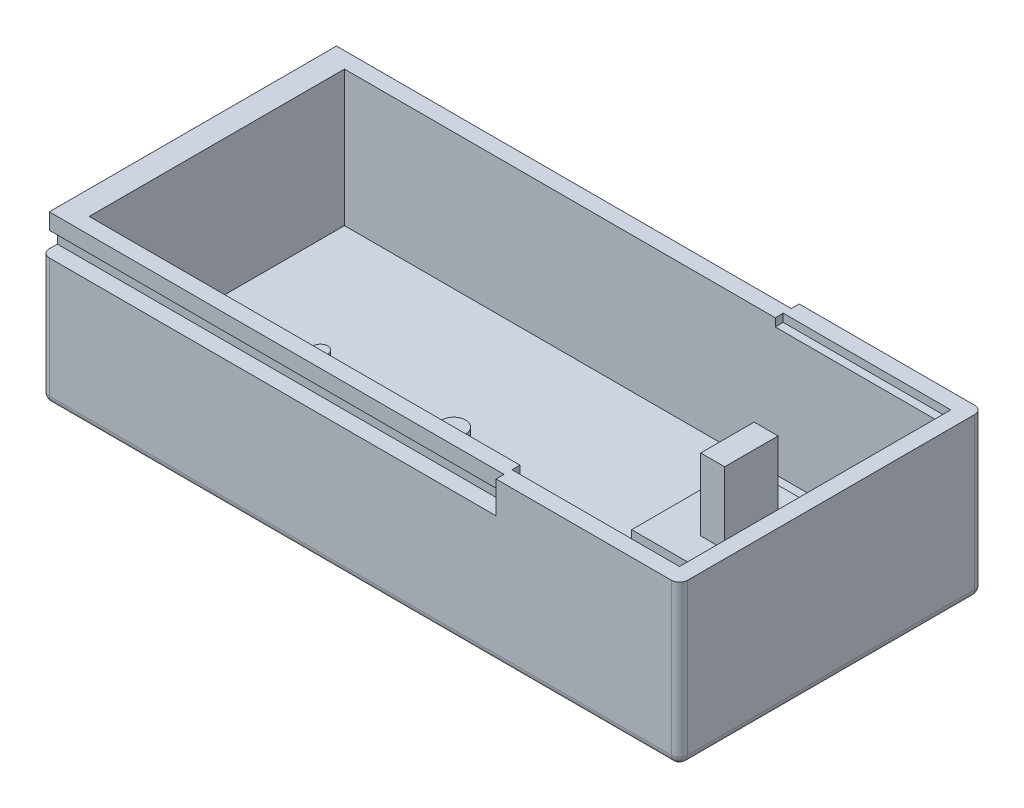
SolidWorks part; units mm, degrees
ref_plane "Front" through (0, 0, 0) normal (0, 0, 1) x (1, 0, 0)
ref_plane "Top" through (0, 0, 0) normal (0, 1, 0) x (1, 0, 0)
ref_plane "Right" through (0, 0, 0) normal (1, 0, 0) x (0, 0, -1)
sketch "Sketch1" plane through (0, 0, 0) normal (0, 1, 0) x (1, 0, 0)
  line L1 (-40, 19) -> (40, 19)
  line L2 (-40, 19) -> (-40, -19)
  line L3 (-40, -19) -> (40, -19)
  line L4 (40, 19) -> (40, -19)
  line L5 (-40, 19) -> (40, -19) construction
  line L6 (-40, -19) -> (40, 19) construction
  point P0 (0, 0)
  dimension "D1" = 80
  dimension "D2" = 38
extrude "Boss-Extrude1" add sketch "Sketch1" along normal mid plane 24
fillet "Fillet1" radius 1 12 edges at (0, -12, -19) (-40, -12, 0) (0, -12, 19) (40, -12, 0) (40, 0, -19) (40, 0, 19) (-40, 0, -19) (-40, 0, 19) (0, 12, 19) (-40, 12, 0) (0, 12, -19) (40, 12, 0)
sketch "Sketch3" plane through (0, 12, 0) normal (0, 1, 0) x (1, 0, 0)
  line L0 (-39, -19) -> (39, -19) construction
  line L1 (17, -19) -> (-40, -19)
  line L2 (17, -19) -> (17, 19)
  line L3 (17, 19) -> (-40, 19)
  line L4 (-40, -19) -> (-40, 19)
  line L5 (17, -19) -> (-40, 19) construction
  line L6 (17, 19) -> (-40, -19) construction
  line L7 (39, 19) -> (-39, 19) construction
  line L8 (-40, 18) -> (-40, -18) construction
  point P4 (-11.5, 0)
  point P11 (17, 0)
  dimension "D1" = 57
extrude "Cut-Extrude1" cut sketch "Sketch3" against normal blind 4
shell "Shell1" thickness 3
sketch "Sketch4" plane through (-40, 0, 0) normal (-1, 0, 0) x (0, 0, 1)
  line L0 (-19, -11) -> (-19, 8) construction
  line L1 (-18, 8) -> (-19, 8)
  line L2 (-18, 8) -> (-18, 6)
  line L3 (-18, 4) -> (-19, 4)
  line L4 (-19, 8) -> (-19, 4)
  line L5 (-18, 8) -> (-19, 4) construction
  line L6 (-18, 4) -> (-19, 8) construction
  line L8 (-18, 4) -> (-17, 4)
  line L10 (-18, 6) -> (-17, 6)
  line L11 (-17, 4) -> (-17, 6)
  line L12 (-18, 4) -> (-17, 6) construction
  line L13 (-18, 6) -> (-17, 4) construction
  point P4 (-18.5, 6)
  point P11 (-17.5, 5)
  point P14 (-17.5, 6)
  point P15 (-17.5, 4)
  dimension "D1" = 4
  dimension "D2" = 1
  dimension "D3" = 2
extrude "Cut-Extrude2" cut sketch "Sketch4" against normal up to surface (57 mm away) up to face at (17, 9.6414, 0)
mirror "Mirror1" about plane through (0, 0, 0) normal (0, 0, 1) of "Cut-Extrude2"
sketch "Sketch5" plane through (0, -9, 0) normal (0, 1, 0) x (1, 0, 0)
  line L0 (-40, 18) -> (-40, -18) construction
  circle A0 centre (-24, 0) radius 0.9
  circle A1 centre (-7.3, 0) radius 1.5
  dimension "D2" = 1.8
  dimension "D4" = 3
  dimension "D1" = 16
  dimension "D3" = 16.7
extrude "Boss-Extrude2" add sketch "Sketch5" along normal blind 1
sketch "Sketch6" plane through (0, 12, 0) normal (0, 1, 0) x (1, 0, 0)
  line L0 (40, 18) -> (40, -18) construction
  line L1 (40, 19) -> (17, 19)
  line L2 (40, 19) -> (40, -19)
  line L3 (40, -19) -> (17, -19)
  line L4 (17, 19) -> (17, -19)
  line L5 (40, 19) -> (17, -19) construction
  line L6 (40, -19) -> (17, 19) construction
  line L7 (39, -19) -> (17, -19) construction
  line L8 (17, -18) -> (17, 18) construction
  line L9 (17, 19) -> (39, 19) construction
  point P0 (28.5, 0)
extrude "Cut-Extrude3" cut sketch "Sketch6" against normal up to surface (4 mm away) up to face at (-10.75, 8, 0)
sketch "Sketch7" plane through (0, -9, 0) normal (0, 1, 0) x (1, 0, 0)
  line L0 (37, -16) -> (37, 16) construction
  line L1 (31.5, 7) -> (22, 7)
  line L2 (31.5, 7) -> (31.5, -7)
  line L3 (31.5, -7) -> (22, -7)
  line L4 (22, 7) -> (22, -7)
  line L5 (31.5, 7) -> (22, -7) construction
  line L6 (31.5, -7) -> (22, 7) construction
  line L7 (37, 16) -> (-37, 16) construction
  line L8 (-37, -16) -> (37, -16) construction
  point P0 (26.75, 0)
  dimension "D1" = 15
  dimension "D2" = 9
  dimension "D3" = 9
  dimension "D4" = 9.5
extrude "Boss-Extrude3" add sketch "Sketch7" along normal blind 8
sketch "Sketch9" plane through (0, 8, 0) normal (0, 1, 0) x (1, 0, 0)
  line L0 (37, 16) -> (-37, 16) construction
  line L1 (17, 17) -> (38, 17)
  line L2 (17, 17) -> (17, -17)
  line L3 (17, -17) -> (38, -17)
  line L4 (38, 17) -> (38, -17)
  line L5 (17, 17) -> (38, -17) construction
  line L6 (17, -17) -> (38, 17) construction
  line L7 (-37, -16) -> (37, -16) construction
  line L8 (37, -16) -> (37, 16) construction
  line L9 (17, 18) -> (17, 19) construction
  point P4 (27.5, 0)
  dimension "D1" = 1
  dimension "D2" = 1
  dimension "D3" = 1
extrude "Cut-Extrude6" cut sketch "Sketch9" against normal blind 1
sketch "Sketch8" plane through (0, -1, 0) normal (0, 1, 0) x (1, 0, 0)
  line L1 (30, 3.35) -> (27, 3.35)
  line L2 (30, 3.35) -> (30, -3.35)
  line L3 (30, -3.35) -> (27, -3.35)
  line L4 (27, 3.35) -> (27, -3.35)
  line L5 (30, 3.35) -> (27, -3.35) construction
  line L6 (30, -3.35) -> (27, 3.35) construction
  line L7 (31.5, 7) -> (22, -7) construction
  line L8 (22, 7) -> (31.5, -7) construction
  point P0 (28.5, 0)
  point P16 (26.75, 0)
  dimension "D1" = 3
  dimension "D2" = 6.7
  dimension "D3" = 1.75
extrude "Boss-Extrude4" add sketch "Sketch8" along normal up to surface (9 mm away) up to face at (8.75, 8, 0)
sketch "Sketch10" plane through (0, -9, 0) normal (0, 1, 0) x (1, 0, 0)
  line L0 (30, 3.35) -> (27, 3.35) construction
  line L3 (-39, -19) -> (39, -19) construction
  line L4 (39, 19) -> (-39, 19) construction
  circle A0 centre (28.5, 11) radius 1
  circle A1 centre (28.5, -11) radius 1
  point P6 (28.5, 3.35)
  dimension "D1" = 2
  dimension "D2" = 2
  dimension "D3" = 8
  dimension "D4" = 8
extrude "Cut-Extrude7" cut sketch "Sketch10" against normal up to next
sketch "Sketch11" plane through (0, -12, 0) normal (0, -1, 0) x (1, 0, 0)
  circle A0 centre (28.5, -11) radius 2
  circle A2 centre (28.5, 11) radius 2
  circle A3 centre (28.5, -11) radius 1 construction
  circle A4 centre (28.5, 11) radius 1 construction
  dimension "D1" = 4
  dimension "D2" = 4
extrude "Cut-Extrude8" cut sketch "Sketch11" against normal blind 2
equation "\"D3@Sketch7\"=\"D2@Sketch7\""
equation "\"D2@Sketch9\"=\"D1@Sketch9\""
equation "\"D3@Sketch9\"=\"D1@Sketch9\""
equation "\"D2@Sketch10\"=\"D1@Sketch10\""
equation "\"D2@Sketch11\"=\"D1@Sketch11\""
equation "\"D4@Sketch10\"=\"D3@Sketch10\""
